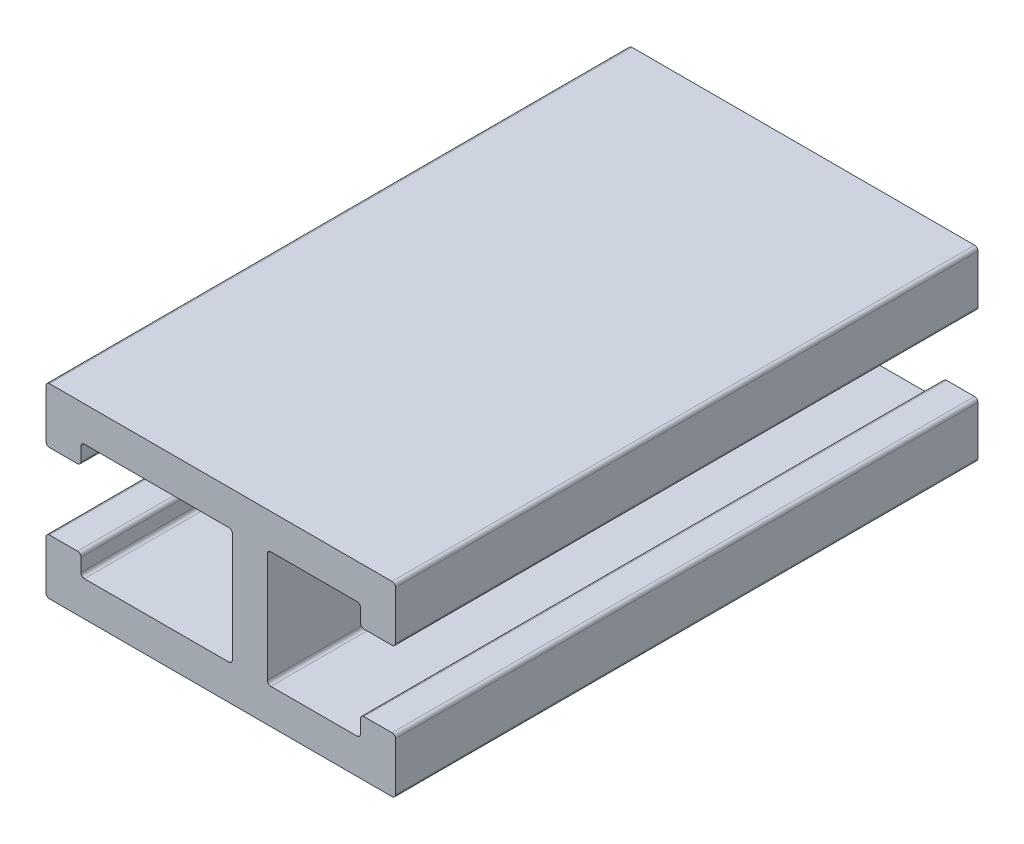
SolidWorks part; units mm, degrees
ref_plane "前视基准面" through (0, 0, 0) normal (0, 0, 1) x (1, 0, 0)
ref_plane "上视基准面" through (0, 0, 0) normal (0, 1, 0) x (1, 0, 0)
ref_plane "右视基准面" through (0, 0, 0) normal (1, 0, 0) x (0, 0, -1)
sketch "草图1" plane through (0, 0, 0) normal (0, 0, 1) x (1, 0, 0)
  line L0 (-11.5772, 5.757) -> (0.8228, 5.757)
  line L1 (1.1228, 5.457) -> (1.1228, -3.943)
  line L2 (0.8228, -4.243) -> (-11.5772, -4.243)
  line L3 (-11.8772, -3.943) -> (-11.8772, -2.793)
  line L4 (-12.1772, -2.493) -> (-14.5772, -2.493)
  line L5 (-14.8772, -2.793) -> (-14.8772, -6.943)
  line L6 (-14.5772, -7.243) -> (14.8228, -7.243)
  line L7 (15.1228, -6.943) -> (15.1228, -2.793)
  line L8 (14.8228, -2.493) -> (12.4228, -2.493)
  line L9 (12.1228, -2.793) -> (12.1228, -3.943)
  line L10 (11.8228, -4.243) -> (4.4228, -4.243)
  line L11 (4.1228, -3.943) -> (4.1228, 5.457)
  line L12 (4.4228, 5.757) -> (11.8228, 5.757)
  line L14 (-11.8772, 5.457) -> (-11.8772, 4.307)
  line L15 (-12.1772, 4.007) -> (-14.5772, 4.007)
  line L16 (-14.8772, 4.307) -> (-14.8772, 8.457)
  line L17 (-14.5772, 8.757) -> (14.8228, 8.757)
  line L18 (15.1228, 8.457) -> (15.1228, 4.307)
  line L19 (14.8228, 4.007) -> (12.4228, 4.007)
  line L20 (12.1228, 4.307) -> (12.1228, 5.457)
  arc A0 (1.1228, 5.457) -> (0.8228, 5.757) centre (0.8228, 5.457) ccw
  arc A1 (0.8228, -4.243) -> (1.1228, -3.943) centre (0.8228, -3.943) ccw
  arc A2 (-11.8772, -3.943) -> (-11.5772, -4.243) centre (-11.5772, -3.943) ccw
  arc A3 (-11.8772, -2.793) -> (-12.1772, -2.493) centre (-12.1772, -2.793) ccw
  arc A4 (-14.5772, -2.493) -> (-14.8772, -2.793) centre (-14.5772, -2.793) ccw
  arc A5 (-14.8772, -6.943) -> (-14.5772, -7.243) centre (-14.5772, -6.943) ccw
  arc A6 (14.8228, -7.243) -> (15.1228, -6.943) centre (14.8228, -6.943) ccw
  arc A7 (15.1228, -2.793) -> (14.8228, -2.493) centre (14.8228, -2.793) ccw
  arc A8 (12.4228, -2.493) -> (12.1228, -2.793) centre (12.4228, -2.793) ccw
  arc A9 (11.8228, -4.243) -> (12.1228, -3.943) centre (11.8228, -3.943) ccw
  arc A10 (4.1228, -3.943) -> (4.4228, -4.243) centre (4.4228, -3.943) ccw
  arc A11 (4.4228, 5.757) -> (4.1228, 5.457) centre (4.4228, 5.457) ccw
  arc A12 (-11.5772, 5.757) -> (-11.8772, 5.457) centre (-11.5772, 5.457) ccw
  arc A13 (-12.1772, 4.007) -> (-11.8772, 4.307) centre (-12.1772, 4.307) ccw
  arc A14 (-14.8772, 4.307) -> (-14.5772, 4.007) centre (-14.5772, 4.307) ccw
  arc A15 (-14.5772, 8.757) -> (-14.8772, 8.457) centre (-14.5772, 8.457) ccw
  arc A16 (15.1228, 8.457) -> (14.8228, 8.757) centre (14.8228, 8.457) ccw
  arc A17 (14.8228, 4.007) -> (15.1228, 4.307) centre (14.8228, 4.307) ccw
  arc A18 (12.1228, 4.307) -> (12.4228, 4.007) centre (12.4228, 4.307) ccw
  arc A19 (12.1228, 5.457) -> (11.8228, 5.757) centre (11.8228, 5.457) ccw
extrude "凸台-拉伸1" add sketch "草图1" along normal blind 50
